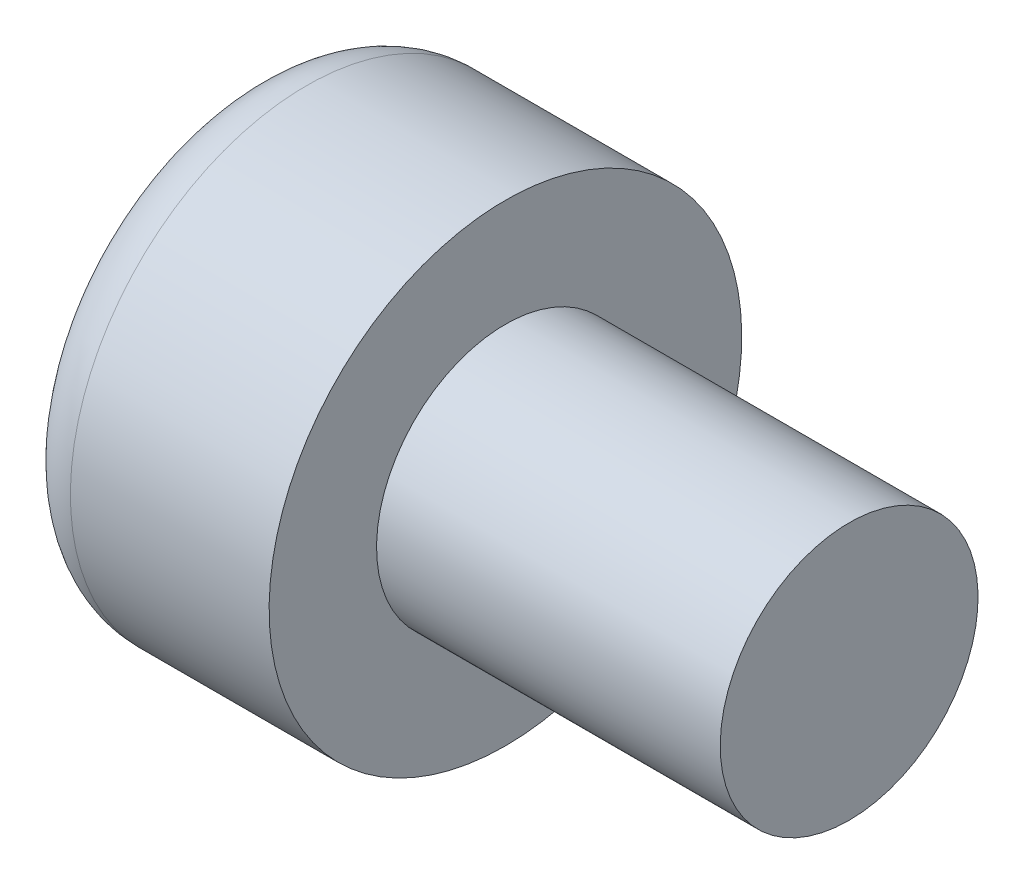
SolidWorks part; units mm, degrees
material "Plain Carbon Steel"
ref_plane "Front Plane" through (0, 0, 0) normal (0, 0, 1) x (1, 0, 0)
ref_plane "Top Plane" through (0, 0, 0) normal (0, 1, 0) x (1, 0, 0)
ref_plane "Right Plane" through (0, 0, 0) normal (1, 0, 0) x (0, 0, -1)
sketch "Sketch1" plane through (0, 0, 0) normal (0, 0, 1) x (1, 0, 0)
  line L0 (0, 0) -> (0, 2.0625)
  line L1 (0.6875, 2.75) -> (3, 2.75)
  line L2 (3, 2.75) -> (3, 1.5)
  line L3 (3, 1.5) -> (7, 1.5)
  line L4 (7, 1.5) -> (7, 0)
  line L5 (7, 0) -> (0, 0) construction
  line L6 (0.6875, 2.0625) -> (0.6875, 1.375) construction
  line L7 (0.6875, 1.375) -> (0.6875, 0.6875) construction
  line L8 (0.6875, 0.6875) -> (0.6875, 0) construction
  line L9 (0.6875, 2.75) -> (0.6875, 2.0625) construction
  line L10 (0, 0) -> (7, 0)
  arc A0 (0, 2.0625) -> (0.6875, 2.75) centre (0.6875, 2.0625) cw
  dimension "D1" = 3
  dimension "D2" = 5.5
  dimension "D3" = 3
  dimension "D4" = 4
revolve "Revolve1" add sketch "Sketch1" angle 360 about L10
sketch "Sketch2" plane through (0, 0, 0) normal (-1, 0, 0) x (0, 0, 1)
  line L1 (0, 1.4434) -> (-1.25, 0.7217)
  line L2 (-1.25, 0.7217) -> (-1.25, -0.7217)
  line L3 (-1.25, -0.7217) -> (0, -1.4434)
  line L4 (0, -1.4434) -> (1.25, -0.7217)
  line L5 (1.25, -0.7217) -> (1.25, 0.7217)
  line L6 (1.25, 0.7217) -> (0, 1.4434)
  circle A0 centre (0, 0) radius 1.25 construction
  dimension "D1" = 2.5
extrude "Cut-Extrude1" cut sketch "Sketch2" against normal blind 1.5
